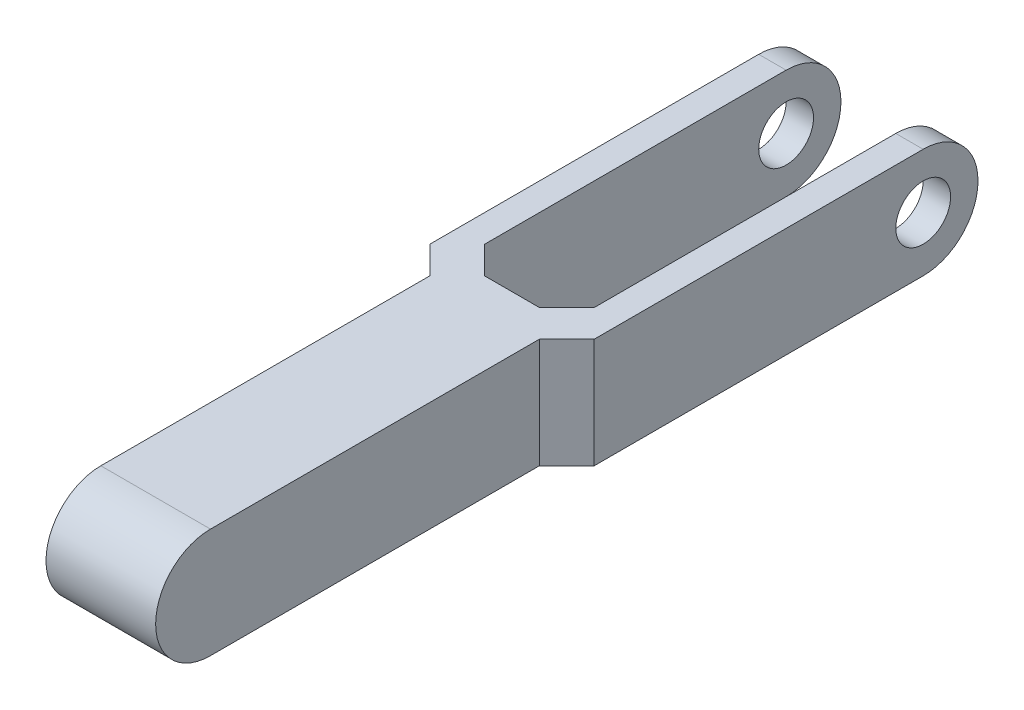
SolidWorks part; units mm, degrees
ref_plane "Front Plane" through (0, 0, 0) normal (0, 0, 1) x (1, 0, 0)
ref_plane "Top Plane" through (0, 0, 0) normal (0, 1, 0) x (1, 0, 0)
ref_plane "Right Plane" through (0, 0, 0) normal (1, 0, 0) x (0, 0, -1)
sketch "Sketch1" plane through (0, 0, 0) normal (1, 0, 0) x (0, 0, -1)
  line L1 (0, 20) -> (250, 20)
  line L2 (0, 20) -> (0, -20)
  line L3 (0, -20) -> (250, -20)
  line L4 (250, 20) -> (250, -20)
  circle A0 centre (0, 0) radius 10
  circle A1 centre (0, 0) radius 20
  circle A2 centre (250, 0) radius 10
  circle A3 centre (250, 0) radius 20
  point P13 (250, 0)
  dimension "D1" = 20
  dimension "D2" = 40
  dimension "D3" = 250
extrude "Boss-Extrude1" add sketch "Sketch1" along normal mid plane 60 contours L2 A1 A0 | L2 A1 A0 | A3 L1 A1 L3 | L4 A3 A2 | L4 A3 A2 | L2 A0 | L2 A0
sketch "Sketch2" plane through (0, 20, 0) normal (0, 1, 0) x (1, 0, 0)
  line L1 (-30, 270) -> (30, 270)
  line L2 (-30, 270) -> (-30, 130)
  line L3 (-30, 130) -> (30, 130)
  line L4 (30, 270) -> (30, 130)
  line L6 (30, 270) -> (-30, 270) construction
  line L7 (-30, -20) -> (30, -20) construction
  line L8 (-20, -20) -> (20, -20)
  line L9 (-20, -20) -> (-20, 120)
  line L10 (-20, 120) -> (20, 120)
  line L11 (20, -20) -> (20, 120)
  line L12 (-30, -20) -> (30, -20) construction
  line L14 (-30, 130) -> (-20, 120)
  line L15 (20, 120) -> (30, 130)
  line L16 (30, 0) -> (30, 250) construction
  line L17 (-30, 270) -> (30, 270)
  line L18 (-30, 270) -> (-30, -20)
  line L19 (-30, -20) -> (30, -20)
  line L20 (30, 270) -> (30, -20)
  line L21 (-30, 0) -> (-30, 250) construction
  line L22 (-20, 270) -> (-20, 140)
  line L23 (20, 270) -> (20, 140)
  line L24 (-20, 120) -> (-10, 130)
  line L25 (20, 120) -> (10, 130)
  line L26 (-20, 140) -> (-10, 130)
  line L27 (20, 140) -> (10, 130)
  point P21 (0, -20)
  point P22 (0, -20)
  line M10 (-30, 0) -> (30, 0)
  line M12 (30, 250) -> (-30, 250)
  line M25 (-30, 250) -> (-30, 0)
  line M26 (30, 0) -> (30, 250)
  dimension "D1" = 140
  dimension "D2" = 40
  dimension "D3" = 45
  dimension "D4" = 45
  dimension "D5" = 10
  dimension "D6" = 45
  dimension "D7" = 45
extrude "Cut-Extrude1" cut sketch "Sketch2" against normal through all contours L23 L17 L22 M12 | L27 L23 L22 L26 L3 M12 | L14 L9 M25 M10 | L15 L11 M10 M26 | L18 L19 L9 M10 | L20 L11 L19 M10
